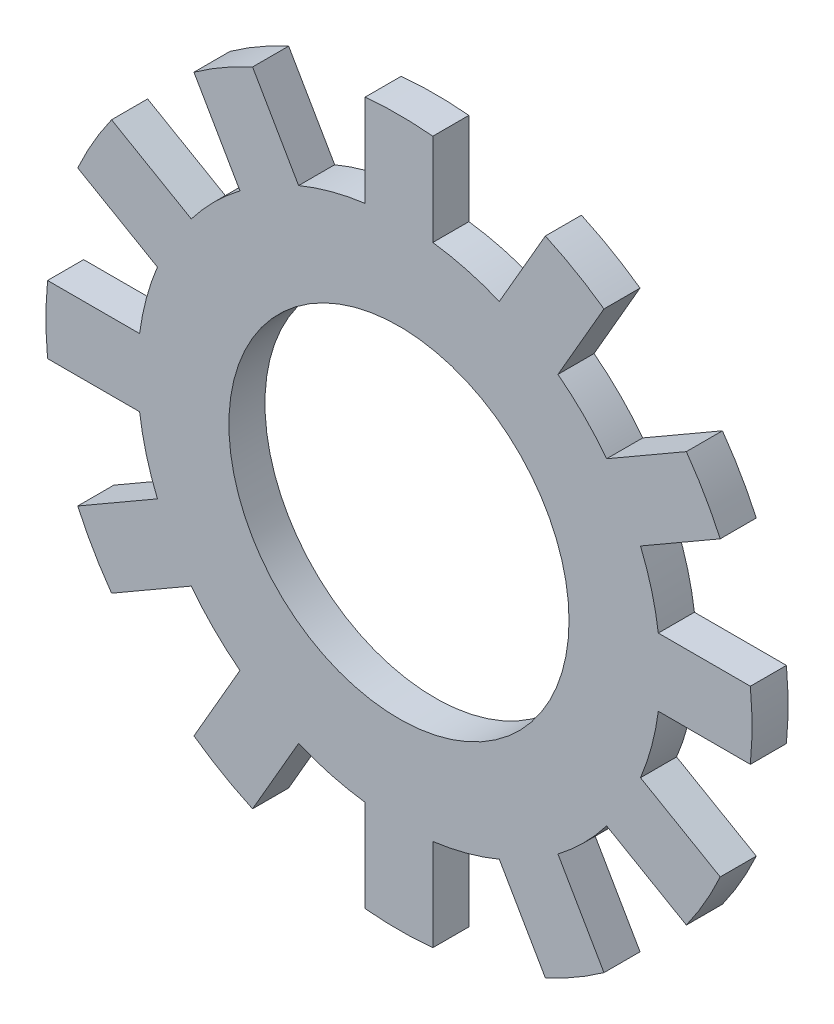
SolidWorks part; units mm, degrees
ref_plane "Front Plane" through (0, 0, 0) normal (0, 0, 1) x (1, 0, 0)
ref_plane "Top Plane" through (0, 0, 0) normal (0, 1, 0) x (1, 0, 0)
ref_plane "Right Plane" through (0, 0, 0) normal (1, 0, 0) x (0, 0, -1)
sketch "Sketch1" plane through (0, 0, 0) normal (0, 0, 1) x (1, 0, 0)
  circle A0 centre (0, 0) radius 3.425 construction
  circle A1 centre (0, 0) radius 1.65
  circle A2 centre (0, 0) radius 2.5375
  dimension "D1" = 5.075
  dimension "A" = 3.3
  dimension "B" = 6.85
extrude "Extrude1" add sketch "Sketch1" along normal blind 0.35
sketch "Sketch2" plane through (0, 0, 0) normal (0, 0, 1) x (1, 0, 0)
  line L0 (0, 0) -> (0, 3.425) construction
  line L1 (0, 0) -> (0.8865, 3.3083) construction
  line L2 (0, 0) -> (-0.8865, 3.3083) construction
  line L3 (-0.6568, 2.451) -> (0, 2.451) construction
  line L4 (-0.3284, 3.4092) -> (-0.3284, 2.5162)
  line L5 (0.3284, 3.4092) -> (0.3284, 2.5162)
  line L6 (-0.3284, 2.5162) -> (0.3284, 2.5162)
  circle A0 centre (0, 0) radius 2.5375 construction
  circle A1 centre (0, 0) radius 2.5375 construction
  circle A2 centre (0, 0) radius 3.425 construction
  arc A3 (0.3284, 3.4092) -> (-0.3284, 3.4092) centre (0, 0) ccw
  dimension "D2" = 15
  dimension "D3" = 15
extrude "Extrude2" add sketch "Sketch2" along normal up to surface (0.35 mm away) up to face at (2.5375, 0, 0.35)
pattern_circular "CirPattern1" count 12 over 360 about axis through (0, 0, 0) along (0, 0, 1) of "Extrude2"
sketch "Sketch3" plane through (0, 0, 0) normal (0, 0, 1) x (1, 0, 0)
  line L0 (-0.3921, 3.4025) -> (-0.3921, 2.507)
  line L1 (0.3921, 3.4025) -> (0.3921, 2.507)
  line L2 (0, 0) -> (0, 3.425) construction
  line L3 (0, 0) -> (1.0584, 3.2574) construction
  line L4 (0, 0) -> (-1.0584, 3.2574) construction
  line L5 (-0.7841, 2.4133) -> (0, 2.4133) construction
  line L6 (-0.3921, 2.507) -> (0.3921, 2.507)
  circle A0 centre (0, 0) radius 3.425 construction
  circle A1 centre (0, 0) radius 2.5375 construction
  circle A2 centre (0, 0) radius 2.5375 construction
  arc A3 (0.3921, 3.4025) -> (-0.3921, 3.4025) centre (0, 0) ccw
  dimension "D2" = 18
  dimension "D3" = 18
extrude "Extrude3" [suppressed] add sketch "Sketch3" along normal up to surface (0.25 mm away)
pattern_circular "CirPattern2" [suppressed] count 10 over 360
equation "\"D1@Sketch1\" =  ( \"B@Sketch1\" + \"A@Sketch1\" )  / 2"
